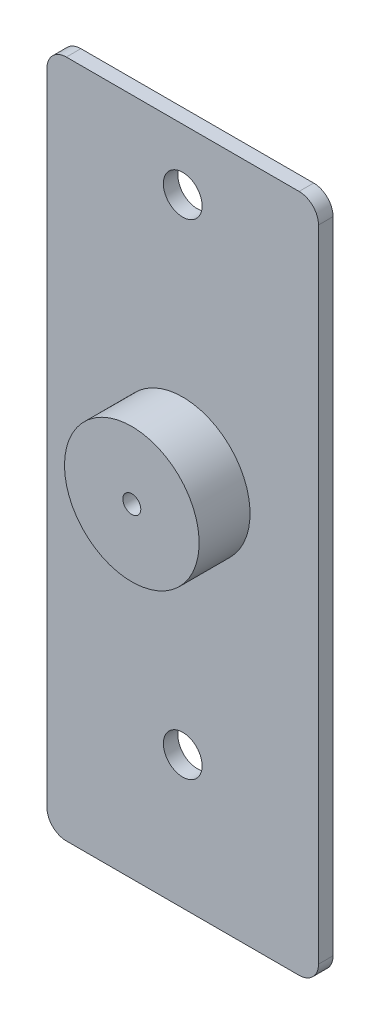
SolidWorks part; units mm, degrees
ref_plane "Front Plane" through (0, 0, 0) normal (0, 0, 1) x (1, 0, 0)
ref_plane "Top Plane" through (0, 0, 0) normal (0, 1, 0) x (1, 0, 0)
ref_plane "Right Plane" through (0, 0, 0) normal (1, 0, 0) x (0, 0, -1)
sketch "Sketch1" plane through (0, 0, 0) normal (0, 0, 1) x (1, 0, 0)
  line L1 (14, 35) -> (-14, 35)
  line L2 (14, 35) -> (14, -35)
  line L3 (14, -35) -> (-14, -35)
  line L4 (-14, 35) -> (-14, -35)
  line L5 (14, 35) -> (-14, -35) construction
  line L6 (14, -35) -> (-14, 35) construction
  point P0 (0, 0)
  dimension "D1" = 70
  dimension "D2" = 28
extrude "Boss-Extrude1" add sketch "Sketch1" against normal blind 1.5 contours L1 L4 L3 L2
sketch "Sketch3" plane through (0, 0, 0) normal (0, 0, 1) x (1, 0, 0)
  circle A0 centre (0, 3.7036) radius 6.9415
  circle A1 centre (0, 3.7036) radius 7.9415 construction
  dimension "D1" = 1
extrude "Boss-Extrude2" add sketch "Sketch3" along normal blind 5.25
sketch "Sketch2" plane through (0, 0, -1.5) normal (0, 0, -1) x (-1, 0, 0)
  circle A0 centre (0.0005, -21.295) radius 2
  circle A1 centre (0.0005, 28.705) radius 2
  circle A2 centre (0, 3.7036) radius 0.925
  dimension "D1" = 1.85
  dimension "D2" = 4
extrude "Cut-Extrude1" cut sketch "Sketch2" against normal through all
fillet "Fillet1" radius 2 4 edges at (14, -35, -0.75) (-14, -35, -0.75) (-14, 35, -0.75) (14, 35, -0.75)
